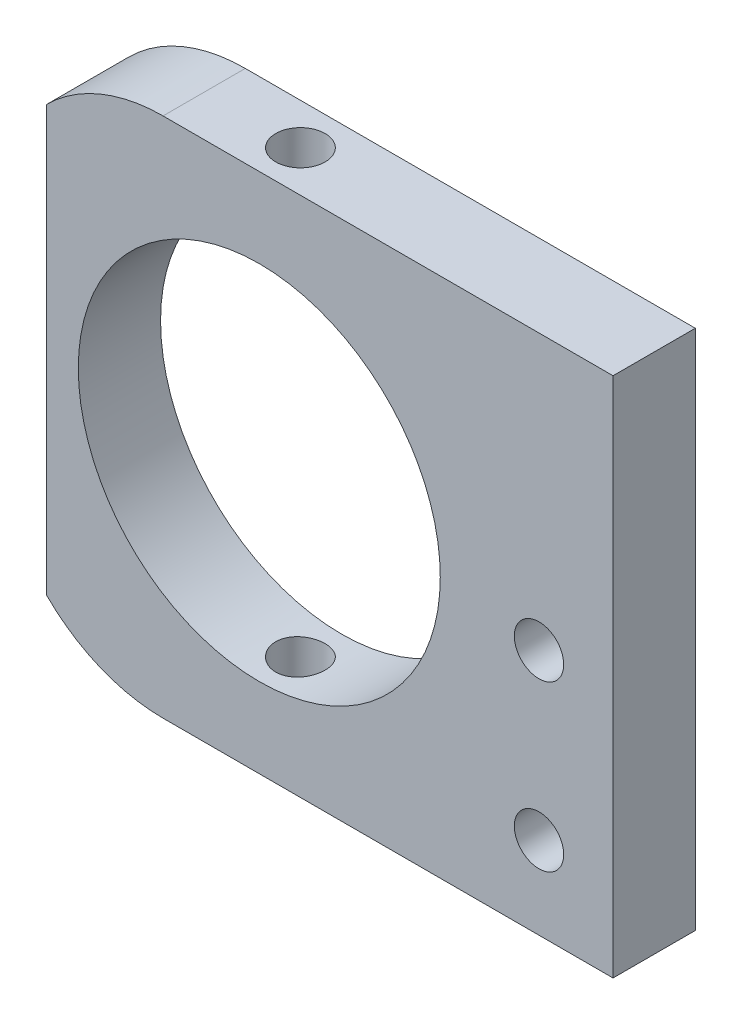
SolidWorks part; units mm, degrees
ref_plane "Alzado" through (0, 0, 0) normal (0, 0, 1) x (1, 0, 0)
ref_plane "Planta" through (0, 0, 0) normal (0, 1, 0) x (1, 0, 0)
ref_plane "Vista lateral" through (0, 0, 0) normal (1, 0, 0) x (0, 0, -1)
sketch "Model" plane through (0, 0, 0) normal (0, 0, 1) x (1, 0, 0)
  line L7 (112.2515, 91.1736) -> (133.9515, 91.1736)
  line L8 (133.9515, 122.8736) -> (112.2515, 122.8736)
  line L10 (133.9515, 91.1736) -> (139.6015, 91.1736)
  line L11 (139.6015, 91.1736) -> (139.6015, 122.8736)
  line L13 (133.9515, 122.8736) -> (139.6015, 122.8736)
  line L17 (105.1804, 119.9446) -> (105.1804, 94.1025)
  arc A7 (112.2515, 91.1736) -> (105.1804, 94.1025) centre (112.2515, 101.1736) cw
  arc A8 (105.1804, 119.9446) -> (112.2515, 122.8736) centre (112.2515, 112.8736) cw
  circle A9 centre (118.1015, 107.0236) radius 11
  circle A10 centre (135.1015, 106.1736) radius 1.5
  circle A11 centre (135.1015, 96.1736) radius 1.5
extrude "Saliente-Extruir1" add sketch "Model" along normal blind 5
sketch "Croquis2" plane through (0, 91.1736, 0) normal (0, -1, 0) x (1, 0, 0)
  circle A0 centre (118.1015, 2.5) radius 1.5
extrude "Cortar-Extruir1" cut sketch "Croquis2" against normal blind 35
